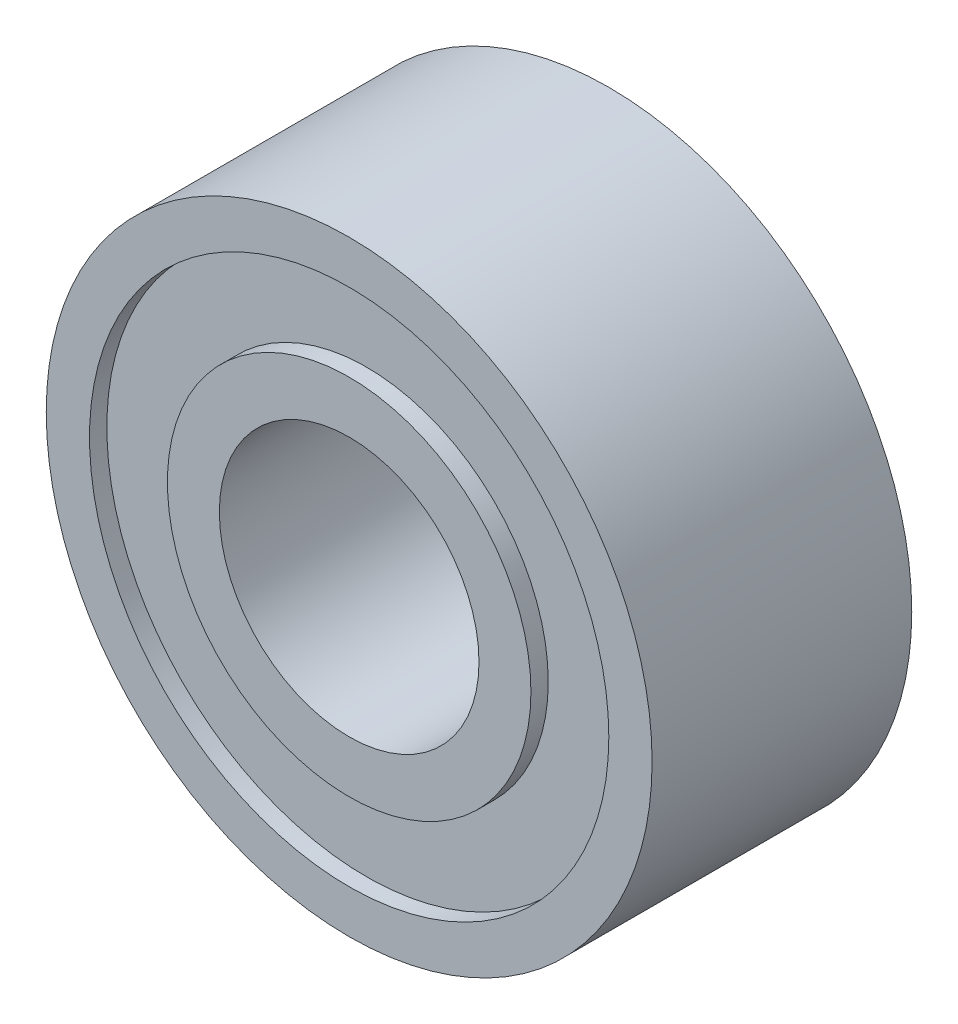
SolidWorks part; units mm, degrees
material "1023 Carbon Steel Sheet (SS)"
ref_plane "Front Plane" through (0, 0, 0) normal (0, 0, 1) x (1, 0, 0)
ref_plane "Top Plane" through (0, 0, 0) normal (0, 1, 0) x (1, 0, 0)
ref_plane "Right Plane" through (0, 0, 0) normal (1, 0, 0) x (0, 0, -1)
sketch "Sketch3" plane through (0, 0, 0) normal (0, 0, 1) x (1, 0, 0)
  circle A0 centre (0, 0) radius 7.5
  circle A1 centre (0, 0) radius 17.5
  dimension "D1" = 15
  dimension "D2" = 35
extrude "Boss-Extrude1" add sketch "Sketch3" along normal blind 15
sketch "Sketch4" plane through (0, 0, 15) normal (0, 0, 1) x (1, 0, 0)
  circle A0 centre (0, 0) radius 10.5
  circle A1 centre (0, 0) radius 15
  dimension "D1" = 21
  dimension "D2" = 30
extrude "Cut-Extrude1" cut sketch "Sketch4" against normal blind 1
sketch "Sketch5" plane through (0, 0, 0) normal (0, 0, -1) x (-1, 0, 0)
  circle A0 centre (0, 0) radius 10.5
  circle A1 centre (0, 0) radius 15
  dimension "D1" = 21
  dimension "D2" = 30
extrude "Cut-Extrude2" cut sketch "Sketch5" against normal blind 1
